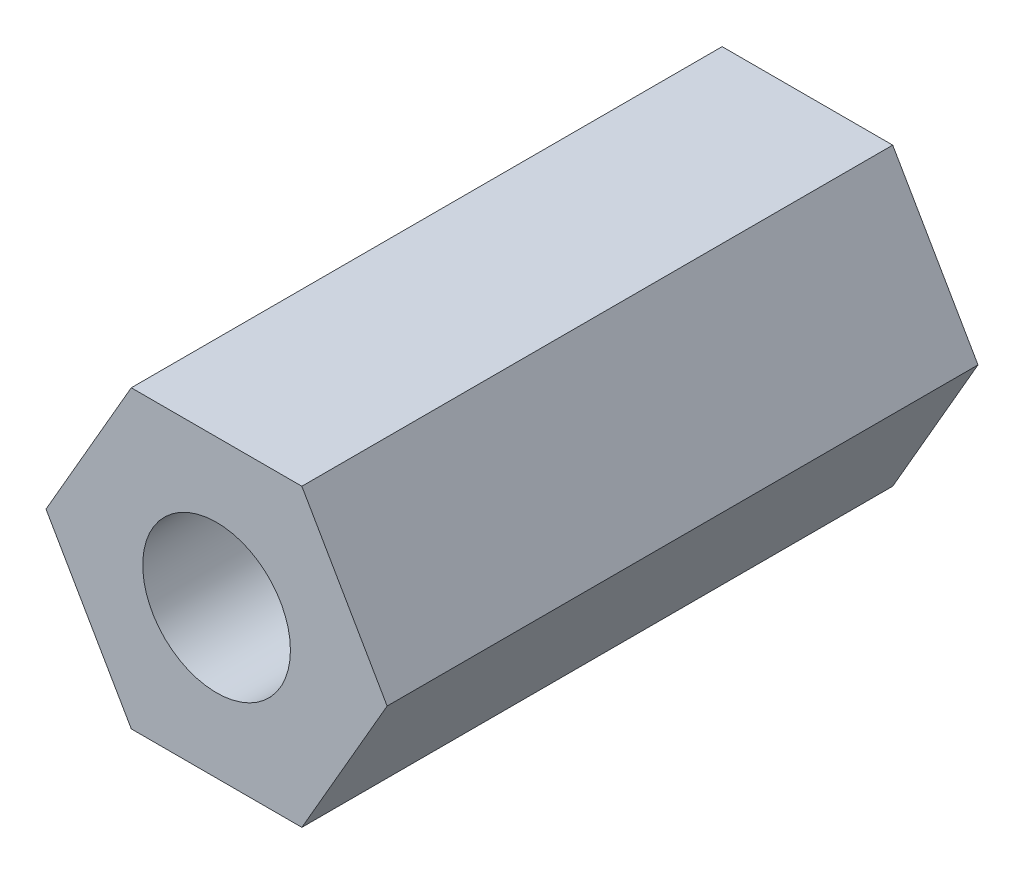
SolidWorks part; units mm, degrees
ref_plane "前视基准面" through (0, 0, 0) normal (0, 0, 1) x (1, 0, 0)
ref_plane "上视基准面" through (0, 0, 0) normal (0, 1, 0) x (1, 0, 0)
ref_plane "右视基准面" through (0, 0, 0) normal (1, 0, 0) x (0, 0, -1)
other "Configuration Table"
sketch "草图1" plane through (0, 0, 0) normal (0, 0, 1) x (1, 0, 0)
  line L1 (3.4641, 0) -> (1.7321, 3)
  line L2 (1.7321, 3) -> (-1.7321, 3)
  line L3 (-1.7321, 3) -> (-3.4641, 0)
  line L4 (-3.4641, 0) -> (-1.7321, -3)
  line L5 (-1.7321, -3) -> (1.7321, -3)
  line L6 (1.7321, -3) -> (3.4641, 0)
  circle A0 centre (0, 0) radius 3 construction
  circle A1 centre (0, 0) radius 1.5
  dimension "D2" = 3
  dimension "D1" = 6
extrude "凸台-拉伸1" add sketch "草图1" along normal blind 12
